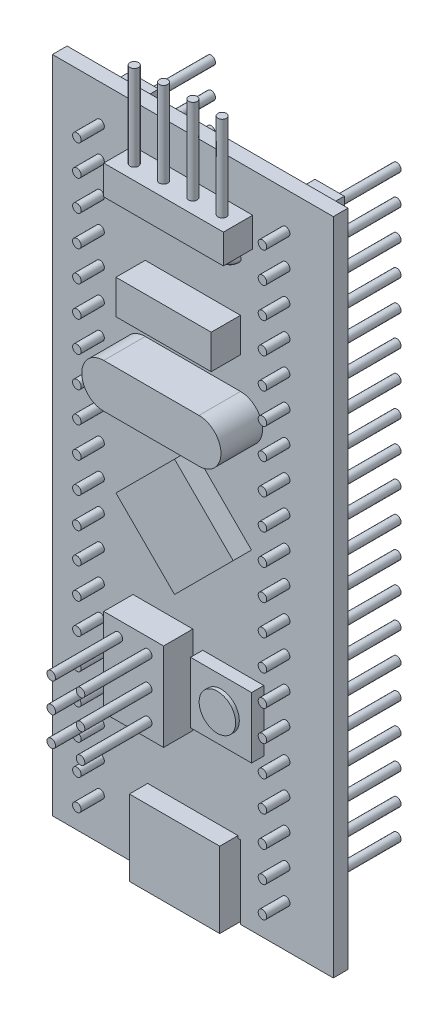
SolidWorks part; units mm, degrees
material "Плата обработки данных, простая"
ref_plane "Спереди" through (0, 0, 0) normal (0, 0, 1) x (1, 0, 0)
ref_plane "Сверху" through (0, 0, 0) normal (0, 1, 0) x (1, 0, 0)
ref_plane "Справа" through (0, 0, 0) normal (1, 0, 0) x (0, 0, -1)
sketch "Эскиз1" plane through (0, 0, 0) normal (0, 0, 1) x (1, 0, 0)
  line L0 (0.4001, -30.8708) -> (0.4001, 23.1292) construction
  line L1 (-11.0999, 23.1292) -> (11.9001, 23.1292)
  line L2 (-11.0999, 23.1292) -> (-11.0999, -30.8708)
  line L3 (-11.0999, -30.8708) -> (11.9001, -30.8708)
  line L4 (11.9001, 23.1292) -> (11.9001, -30.8708)
  line L5 (-11.0999, -3.8708) -> (11.9001, -3.8708) construction
  dimension "D1" = 23
  dimension "D2" = 54
extrude "Бобышка-Вытянуть1" add sketch "Эскиз1" along normal blind 1.2
sketch "Эскиз2" plane through (0, 0, 0) normal (0, 0, -1) x (-1, 0, 0)
  line L0 (-0.4001, 23.1292) -> (-0.4001, -30.8708) construction
  line L1 (-11.9001, 23.1292) -> (11.0999, 23.1292) construction
  line L2 (11.0999, -30.8708) -> (-11.9001, -30.8708) construction
  line L3 (-9.2001, 21.4292) -> (-9.2001, -29.1708)
  line L4 (5.9999, 21.4292) -> (8.3999, 21.4292)
  line L5 (5.9999, 21.4292) -> (5.9999, -29.1708)
  line L6 (5.9999, -29.1708) -> (8.3999, -29.1708)
  line L7 (8.3999, 21.4292) -> (8.3999, -29.1708)
  line L8 (-6.8001, -29.1708) -> (-9.2001, -29.1708)
  line L9 (-6.8001, 21.4292) -> (-6.8001, -29.1708)
  line L10 (-6.8001, 21.4292) -> (-9.2001, 21.4292)
  line L11 (-0.4001, -3.8708) -> (-7.8164, -3.8708) construction
  point P16 (-6.8001, -3.8708)
  dimension "D1" = 2.4
  dimension "D2" = 50.6
  dimension "D3" = 17.6
extrude "Бобышка-Вытянуть2" add sketch "Эскиз2" along normal blind 2.4
sketch "Эскиз3" plane through (0, 0, -2.4) normal (0, 0, -1) x (-1, 0, 0)
  circle A0 centre (-8.0001, 20.1329) radius 0.35
  circle A1 centre (7.1999, 20.1329) radius 0.35
  circle A2 centre (7.1999, 17.6329) radius 0.35
  circle A3 centre (7.1999, 15.1329) radius 0.35
  circle A4 centre (7.1999, 12.6329) radius 0.35
  circle A5 centre (7.1999, 10.1329) radius 0.35
  circle A6 centre (7.1999, 7.6329) radius 0.35
  circle A7 centre (7.1999, 5.1329) radius 0.35
  circle A8 centre (7.1999, 2.6329) radius 0.35
  circle A9 centre (7.1999, 0.1329) radius 0.35
  circle A10 centre (7.1999, -2.3671) radius 0.35
  circle A11 centre (7.1999, -4.8671) radius 0.35
  circle A12 centre (7.1999, -7.3671) radius 0.35
  circle A13 centre (7.1999, -9.8671) radius 0.35
  circle A14 centre (7.1999, -12.3671) radius 0.35
  circle A15 centre (7.1999, -14.8671) radius 0.35
  circle A16 centre (7.1999, -17.3671) radius 0.35
  circle A17 centre (7.1999, -19.8671) radius 0.35
  circle A18 centre (7.1999, -22.3671) radius 0.35
  circle A19 centre (7.1999, -24.8671) radius 0.35
  circle A20 centre (7.1999, -27.3671) radius 0.35
  circle A21 centre (-8.0001, 17.6329) radius 0.35
  circle A22 centre (-8.0001, 15.1329) radius 0.35
  circle A23 centre (-8.0001, 12.6329) radius 0.35
  circle A24 centre (-8.0001, 10.1329) radius 0.35
  circle A25 centre (-8.0001, 7.6329) radius 0.35
  circle A26 centre (-8.0001, 5.1329) radius 0.35
  circle A27 centre (-8.0001, 2.6329) radius 0.35
  circle A28 centre (-8.0001, 0.1329) radius 0.35
  circle A29 centre (-8.0001, -2.3671) radius 0.35
  circle A30 centre (-8.0001, -4.8671) radius 0.35
  circle A31 centre (-8.0001, -7.3671) radius 0.35
  circle A32 centre (-8.0001, -9.8671) radius 0.35
  circle A33 centre (-8.0001, -12.3671) radius 0.35
  circle A34 centre (-8.0001, -14.8671) radius 0.35
  circle A35 centre (-8.0001, -17.3671) radius 0.35
  circle A36 centre (-8.0001, -19.8671) radius 0.35
  circle A37 centre (-8.0001, -22.3671) radius 0.35
  circle A38 centre (-8.0001, -24.8671) radius 0.35
  circle A39 centre (-8.0001, -27.3671) radius 0.35
  dimension "D1" = 0.7
  dimension "D2" = 2
  dimension "D3" = 20
extrude "Бобышка-Вытянуть3" add sketch "Эскиз3" along normal mid plane 11
sketch "Эскиз4" plane through (0, 0, 1.2) normal (0, 0, 1) x (1, 0, 0)
  line L0 (0.4001, 23.1292) -> (0.4001, -30.8708) construction
  line L1 (-4.4999, 19.9292) -> (5.3001, 19.9292)
  line L2 (-4.4999, 19.9292) -> (-4.4999, 17.5292)
  line L3 (-4.4999, 17.5292) -> (5.3001, 17.5292)
  line L4 (5.3001, 19.9292) -> (5.3001, 17.5292)
  line L5 (-4.4999, -11.8708) -> (0.4001, -11.8708)
  line L6 (-4.4999, -11.8708) -> (-4.4999, -19.0708)
  line L7 (-4.4999, -19.0708) -> (0.4001, -19.0708)
  line L8 (0.4001, -11.8708) -> (0.4001, -19.0708)
  line L9 (-3.4999, 12.3292) -> (4.3001, 12.3292)
  line L10 (-3.4999, 12.3292) -> (-3.4999, 9.5292)
  line L11 (-3.4999, 9.5292) -> (4.3001, 9.5292)
  line L12 (4.3001, 12.3292) -> (4.3001, 9.5292)
  line L13 (11.9001, 23.1292) -> (-11.0999, 23.1292) construction
  line L14 (-11.0999, -30.8708) -> (11.9001, -30.8708) construction
  point P18 (5.3001, 18.7292)
  dimension "D1" = 2.4
  dimension "D2" = 4.9
  dimension "D3" = 4.9
  dimension "D4" = 4.9
  dimension "D5" = 7.8
  dimension "D6" = 3.9
  dimension "D7" = 5.6
  dimension "D8" = 10.4
  dimension "D9" = 2.8
  dimension "D10" = 19
  dimension "D11" = 7.2
extrude "Бобышка-Вытянуть4" add sketch "Эскиз4" along normal blind 2.4
sketch "Эскиз5" plane through (0, 19.9292, 0) normal (0, 1, 0) x (1, 0, 0)
  line L0 (5.3001, -3.6) -> (-4.4999, -3.6) construction
  circle A0 centre (-3.1999, -2.4) radius 0.35
  circle A1 centre (-0.7999, -2.4) radius 0.35
  circle A2 centre (1.6001, -2.4) radius 0.35
  circle A3 centre (4.0001, -2.4) radius 0.35
  point P4 (0.4001, -3.6)
  dimension "D1" = 0.7
  dimension "D2" = 3.6
  dimension "D3" = 4
extrude "Бобышка-Вытянуть5" add sketch "Эскиз5" along normal blind 7
sketch "Эскиз6" plane through (0, 17.5292, 0) normal (0, -1, 0) x (1, 0, 0)
  line L0 (0.4001, 3.6) -> (0.4001, 1.2) construction
  line L1 (-4.4999, 1.2) -> (5.3001, 1.2) construction
  circle A0 centre (-3.1999, 2.4) radius 0.35
  circle A1 centre (-0.7999, 2.4) radius 0.35
  circle A2 centre (1.6001, 2.4) radius 0.35
  circle A3 centre (4.0001, 2.4) radius 0.35
  dimension "D1" = 0.7
  dimension "D2" = 3.6
  dimension "D3" = 4
revolve "Повернуть1" add sketch "Эскиз6" angle 360 about L1
sketch "Эскиз7" plane through (0, 0, 3.6) normal (0, 0, 1) x (1, 0, 0)
  line L0 (-4.4999, -11.8708) -> (-4.4999, -19.0708) construction
  line L1 (0.4001, -11.8708) -> (-4.4999, -11.8708) construction
  circle A0 centre (-3.2999, -13.0708) radius 0.35
  circle A1 centre (-0.8999, -13.0708) radius 0.35
  circle A2 centre (-0.8999, -15.4708) radius 0.35
  circle A3 centre (-0.8999, -17.8708) radius 0.35
  circle A4 centre (-3.2999, -15.4708) radius 0.35
  circle A5 centre (-3.2999, -17.8708) radius 0.35
  dimension "D1" = 0.7
  dimension "D2" = 1.2
  dimension "D3" = 1.2
  dimension "D4" = 2
  dimension "D5" = 3
extrude "Бобышка-Вытянуть6" add sketch "Эскиз7" along normal mid plane 11
sketch "Эскиз8" plane through (0, 0, 1.2) normal (0, 0, 1) x (1, 0, 0)
  line L0 (0.4001, 23.1292) -> (0.4001, -30.8708) construction
  line L1 (11.9001, 23.1292) -> (-11.0999, 23.1292) construction
  line L2 (-11.0999, -30.8708) -> (11.9001, -30.8708) construction
  line L3 (-11.0999, -3.8708) -> (11.9001, -3.8708) construction
  line L4 (-11.0999, 23.1292) -> (-11.0999, -30.8708) construction
  line L5 (11.9001, -30.8708) -> (11.9001, 23.1292) construction
  line L6 (-4.3999, -3.8708) -> (0.4001, 0.9292)
  line L7 (0.4001, 0.9292) -> (5.2001, -3.8708)
  line L8 (5.2001, -3.8708) -> (0.4001, -8.6708)
  line L9 (0.4001, -8.6708) -> (-4.3999, -3.8708)
  line L11 (-3.2999, -30.8708) -> (4.1001, -30.8708)
  line L12 (-3.2999, -30.8708) -> (-3.2999, -24.6708)
  line L13 (-3.2999, -24.6708) -> (4.1001, -24.6708)
  line L14 (4.1001, -30.8708) -> (4.1001, -24.6708)
  point P20 (0.4001, -24.6708)
  dimension "D1" = 45
  dimension "D2" = 4.8
  dimension "D3" = 7.4
  dimension "D4" = 6.2
extrude "Бобышка-Вытянуть7" add sketch "Эскиз8" along normal blind 1.5
sketch "Эскиз9" plane through (0, 0, 1.2) normal (0, 0, 1) x (1, 0, 0)
  line L0 (-3.4999, 5.1292) -> (4.3001, 5.1292) construction
  line L1 (-3.4999, 6.9292) -> (4.3001, 6.9292)
  line L2 (-3.4999, 3.3292) -> (4.3001, 3.3292)
  line L3 (4.3001, 12.3292) -> (-3.4999, 12.3292) construction
  arc A0 (-3.4999, 6.9292) -> (-3.4999, 3.3292) centre (-3.4999, 5.1292) ccw
  arc A1 (4.3001, 3.3292) -> (4.3001, 6.9292) centre (4.3001, 5.1292) ccw
  point P2 (0.4001, 5.1292)
  dimension "D1" = 3.6
  dimension "D2" = 9
extrude "Бобышка-Вытянуть8" add sketch "Эскиз9" along normal blind 3.4
sketch "Эскиз10" plane through (0, 0, 1.2) normal (0, 0, 1) x (1, 0, 0)
  line L1 (1.2093, -12.9708) -> (6.2093, -12.9708)
  line L2 (1.2093, -12.9708) -> (1.2093, -17.9708)
  line L3 (1.2093, -17.9708) -> (6.2093, -17.9708)
  line L4 (6.2093, -12.9708) -> (6.2093, -17.9708)
  circle A0 centre (3.7093, -15.4708) radius 2.5 construction
  dimension "D1" = 5
extrude "Бобышка-Вытянуть9" add sketch "Эскиз10" along normal blind 1
sketch "Эскиз11" plane through (0, 0, 2.2) normal (0, 0, 1) x (1, 0, 0)
  circle A0 centre (3.7093, -15.4708) radius 1.4951
extrude "Бобышка-Вытянуть10" add sketch "Эскиз11" along normal blind 0.3
sketch "Эскиз12" plane through (0, -30.8708, 0) normal (0, -1, 0) x (1, 0, 0)
  line L0 (-3.484, 1.2) -> (-3.484, 0)
  line L1 (-4.4999, 1.2) -> (0.4001, 1.2) construction
  line L2 (-11.0999, 0) -> (11.9001, 0) construction
  line L4 (-2.7206, 0.1855) -> (-3.2999, 0.727)
  line L5 (-3.2999, 0.727) -> (-3.2999, 1.2)
  line L6 (-3.2999, 1.2) -> (-3.484, 1.2)
  line L7 (0.4001, 0) -> (0.4001, 2.7) construction
  line L8 (-3.2999, 2.7) -> (4.1001, 2.7) construction
  line L9 (4.1001, 0.727) -> (4.1001, 1.2)
  line L10 (3.5208, 0.1855) -> (4.1001, 0.727)
  line L12 (4.2842, 1.2) -> (4.2842, 0)
  line L13 (4.1001, 1.2) -> (4.2842, 1.2)
  line L14 (-2.7206, 0.1855) -> (3.5208, 0.1855)
  line L15 (4.2842, 0) -> (-3.484, 0)
extrude "Вырез-Вытянуть1" cut sketch "Эскиз12" against normal blind 6
